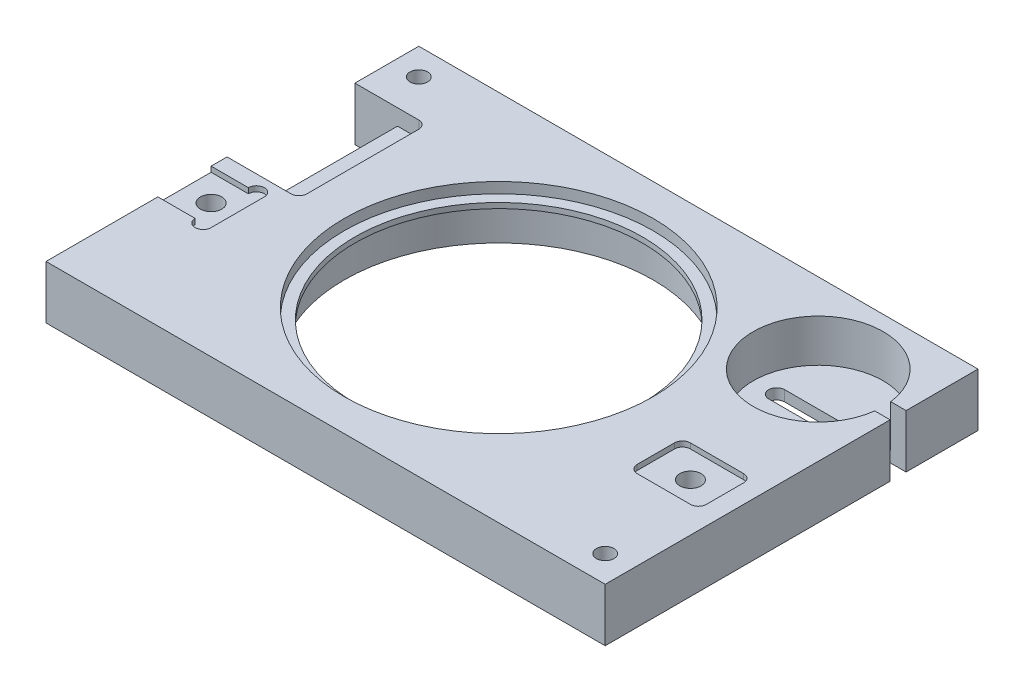
SolidWorks part; units mm, degrees
material "Alliage 1060"
ref_plane "Plan de face" through (0, 0, 0) normal (0, 0, 1) x (1, 0, 0)
ref_plane "Plan de dessus" through (0, 0, 0) normal (0, 1, 0) x (1, 0, 0)
ref_plane "Plan de droite" through (0, 0, 0) normal (1, 0, 0) x (0, 0, -1)
sketch "Esquisse1" plane through (0, 0, 0) normal (0, 1, 0) x (1, 0, 0)
  line L1 (-50, 35) -> (55, 35)
  line L2 (-50, 35) -> (-50, -35)
  line L3 (-50, -35) -> (55, -35)
  line L4 (55, 35) -> (55, -35)
  line L5 (-50, -27.65) -> (-50, -17.65) construction
  circle A0 centre (0, 0) radius 27
  dimension "D1" = 50
  dimension "D4" = 54
  dimension "D2" = 35
  dimension "D3" = 35
  dimension "D5" = 55
extrude "Extrusion1" add sketch "Esquisse1" along normal blind 10
sketch "Esquisse2" plane through (0, 10, 0) normal (0, 1, 0) x (-1, 0, 0)
  circle A1 centre (-40, -20) radius 12.2
extrude "Enlèv. mat.-Extru.1" cut sketch "Esquisse2" against normal up to surface (8 mm away)
sketch "Esquisse3" plane through (0, 0, 0) normal (0, 1, 0) x (1, 0, 0)
  line L0 (32.2, 18.5) -> (55, 18.5)
  line L1 (55, -35) -> (55, 35) construction
  line L2 (32.9, 20.2) -> (31.5, 19.8) construction
  line L3 (55, 18.5) -> (55, 21.5)
  line L4 (55, 21.5) -> (32.2, 21.5)
  arc A0 (32.2, 21.5) -> (32.2, 18.5) centre (32.2, 20) ccw
  circle A2 centre (45, -9) radius 2
  circle A3 centre (-45, -9) radius 2
  dimension "D1" = 1.5
  dimension "D2" = 4
extrude "Enlèv. mat.-Extru.2" cut sketch "Esquisse3" along normal through all
sketch "Esquisse4" plane through (0, 10, 0) normal (0, 1, 0) x (-1, 0, 0)
  line L0 (-50, 14) -> (-40, 14)
  line L2 (-38.5, 12.5) -> (-38.5, 5.5)
  line L3 (-40, 4) -> (-50, 4)
  line L4 (-51.5, 5.5) -> (-51.5, 12.5)
  line L5 (50, 14) -> (43, 14)
  line L8 (40, 14) -> (40, 4)
  line L10 (43, 4) -> (50, 4)
  line L11 (50, 4) -> (50, 14)
  arc A0 (-40, 14) -> (-38.5, 12.5) centre (-40, 12.5) cw
  arc A1 (-38.5, 5.5) -> (-40, 4) centre (-40, 5.5) cw
  arc A2 (-50, 4) -> (-51.5, 5.5) centre (-50, 5.5) cw
  arc A3 (-51.5, 12.5) -> (-50, 14) centre (-50, 12.5) cw
  arc A4 (43, 14) -> (40, 14) centre (41.5, 14) ccw
  arc A5 (40, 4) -> (43, 4) centre (41.5, 4) ccw
extrude "Enlèv. mat.-Extru.3" cut sketch "Esquisse4" against normal blind 1
sketch "Esquisse5" plane through (0, 0, 0) normal (0, 1, 0) x (1, 0, 0)
  circle A1 centre (0, 0) radius 29 construction
  circle A2 centre (0, 0) radius 29
extrude "Enlèv. mat.-Extru.4" cut sketch "Esquisse5" along normal up to surface (7 mm away)
sketch "Esquisse6" plane through (0, 10, 0) normal (0, 1, 0) x (-1, 0, 0)
  circle A0 centre (0, 0) radius 29 construction
  circle A1 centre (0, 0) radius 29
extrude "Enlèv. mat.-Extru.6" cut sketch "Esquisse6" against normal offset from surface (2 mm away) 1 up to face at (27, 7, 0)
sketch "Esquisse7" plane through (0, 0, 0) normal (0, 1, 0) x (1, 0, 0)
  line L0 (-50, -1) -> (-42, -1)
  line L2 (-42, -1) -> (-42, 23)
  line L4 (-50, 23) -> (-42, 23)
  line L5 (-50, -1) -> (-50, 23)
  line L6 (-50, 35) -> (-50, -35) construction
  line L9 (-43, -4) -> (-50, -4) construction
  line L10 (55, 35) -> (-50, 35) construction
  dimension "D2" = 3
  dimension "D3" = 12
extrude "Enlèv. mat.-Extru.7" cut sketch "Esquisse7" along normal up to next
sketch "Esquisse8" plane through (0, 10, 0) normal (0, 1, 0) x (-1, 0, 0)
  line L0 (50, -23) -> (38, -23)
  line L1 (36.5, -21.5) -> (36.5, -0.5)
  line L2 (38, 1) -> (50, 1)
  line L3 (50, 1) -> (50, -23)
  arc A0 (38, -23) -> (36.5, -21.5) centre (38, -21.5) cw
  arc A1 (36.5, -0.5) -> (38, 1) centre (38, -0.5) cw
  dimension "D2" = 1.5
extrude "Enlèv. mat.-Extru.8" cut sketch "Esquisse8" against normal blind 3
hole_wizard "Trou taraudé M4x0.71" positions "Esquisse10" profile "Esquisse9" tap size "M4x0.7" standard "ISO"
sketch "Esquisse10" plane through (-42, 0, 0) normal (-1, 0, 0) x (0, 0, 1)
  line L0 (1, 0) -> (-23, 7) construction
  point P0 (-11, 3.5)
sketch "Esquisse9" plane through (-42, 3.5, -11) normal (0, 1, 0) x (0, 0, 1)
  line L0 (0, 0) -> (0, 13.0914)
  line L1 (0, 13.0914) -> (1.65, 12.1)
  line L2 (1.65, 12.1) -> (1.65, 0)
  line L5 (1.65, 0) -> (0, 0)
  line L10 (0, 13.0914) -> (-1.65, 12.1) construction
  line L11 (0, -6.35) -> (0, 107.95) construction
  dimension "Diamètre du trou pour taraudage" = 3.3
  dimension "Profondeur du trou pour taraudage" = 12.1
  dimension "Angle de pointe" = 118
cosmetic thread "Filetage de perçage1" parameters "D1"=10, "D2"=4
hole_wizard "Trou taraudé M4x0.72" positions "Esquisse13" profile "Esquisse12" tap size "M4x0.7" standard "ISO" end condition through all
sketch "Esquisse13" plane through (0, 0, 0) normal (0, -1, 0) x (1, 0, 0)
  line L0 (55, -35) -> (-50, -35) construction
  line L1 (-50, -35) -> (-50, -23) construction
  line L2 (-50, 35) -> (55, 35) construction
  line L3 (55, 35) -> (55, -18.5) construction
  point P0 (-45, -30)
  point P1 (50, 30)
  dimension "D1" = 5
  dimension "D2" = 5
  dimension "D3" = 5
  dimension "D4" = 5
sketch "Esquisse12" plane through (-45, 0, -30) normal (1, 0, 0) x (0, 0, -1)
  line L0 (0, 0) -> (0, 10)
  line L1 (0, 10) -> (1.65, 10)
  line L2 (1.65, 10) -> (1.65, 0)
  line L5 (1.65, 0) -> (0, 0)
  line L11 (0, -6.35) -> (0, 107.95) construction
  dimension "Diamètre du trou pour taraudage jusqu'au prochain" = 3.3
  dimension "Profondeur du trou pour taraudage jusqu'au prochain" = 10
cosmetic thread "Filetage de perçage2" parameters "D2"=4
cosmetic thread "Filetage de perçage3" parameters "D2"=4
